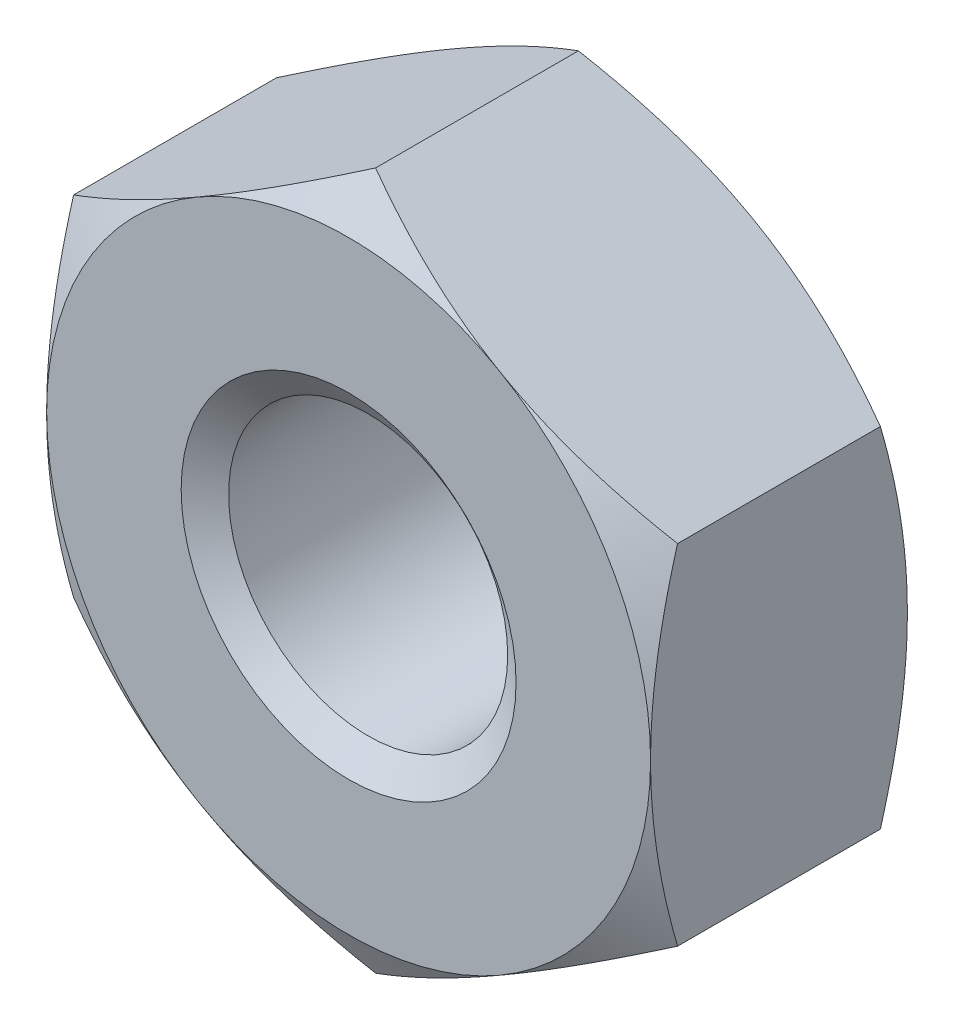
SolidWorks part; units mm, degrees
ref_plane "Plane1" through (0, 0, 0) normal (0, 0, 1) x (1, 0, 0)
ref_plane "Plane2" through (0, 0, 0) normal (0, 1, 0) x (1, 0, 0)
ref_plane "Plane3" through (0, 0, 0) normal (1, 0, 0) x (0, 0, -1)
sketch "BaseNutSke" plane through (0, 0, 0) normal (0, 0, 1) x (1, 0, 0)
  line L6 (2.705, 1.5617) -> (2.705, -1.5617)
  line L7 (-2.705, 1.5617) -> (-2.705, -1.5617)
  line L8 (2.705, 1.5617) -> (0, 3.1235)
  line L9 (0, 3.1235) -> (-2.705, 1.5617)
  line L10 (-2.705, -1.5617) -> (0, -3.1235)
  line L11 (0, -3.1235) -> (2.705, -1.5617)
  circle A0 centre (0, 0) radius 1.25
  dimension "D4" = 2.705
  dimension "Tap_drill" = 2.5
  dimension "D1" = 120
  dimension "D2" = 2.705
  dimension "D3" = 2.705
  dimension "Width_flats" = 5.41
extrude "BaseNut" add sketch "BaseNutSke" against normal blind 2.3
cosmetic thread "ThreadCosmetic"
sketch "Sketch4" plane through (0, 0, 0) normal (1, 0, 0) x (0, 0, -1)
  line L0 (2.3, 2.705) -> (2.29, 2.705)
  line L1 (2.3, 2.705) -> (2.3, 13.1235)
  line L2 (2.29, 13.1235) -> (2.3, 13.1235)
  line L3 (2.29, 13.1235) -> (2.29, 2.705)
  line L4 (0, 0) -> (34.925, 0) construction
  line L6 (2.3, 1.5617) -> (2.3, 3.1235) construction
  line L7 (0, 2.705) -> (-10, 2.705)
  line L8 (0, 1.5617) -> (0, 3.1235) construction
  line L9 (0.2416, 3.1235) -> (0.2416, 13.1235)
  line L10 (0.2416, 13.1235) -> (-10, 13.1235)
  line L11 (-10, 13.1235) -> (-10, 2.705)
  line L12 (0, 2.705) -> (0.2416, 3.1235)
  line L14 (0, 1.5617) -> (0, -1.5617) construction
  line L15 (2.3, 3.1235) -> (0, 3.1235) construction
  dimension "D1" = 2.705
  dimension "D2" = 30
  dimension "Bearing_ht" = 0.01
  dimension "D3" = 10
  dimension "D4" = 10
revolve "Bearing-Face" [suppressed] cut sketch "Sketch4" angle 360 about L4
sketch "Sketch3" plane through (0, 0, 0) normal (1, 0, 0) x (0, 0, -1)
  line L0 (2.3, 2.705) -> (2.0584, 3.1235)
  line L1 (2.0584, 3.1235) -> (2.0584, 13.1235)
  line L2 (2.0584, 13.1235) -> (12.3, 13.1235)
  line L3 (12.3, 13.1235) -> (12.3, 2.705)
  line L4 (12.3, 2.705) -> (2.3, 2.705)
  line L5 (2.3, 1.5617) -> (2.3, 3.1235) construction
  line L6 (2.3, 3.1235) -> (0, 3.1235) construction
  line L7 (0, 0) -> (38.6776, 0) construction
  line L8 (2.3, 0) -> (0, 0) construction
  line L9 (1.15, 3.1235) -> (1.15, 44.222) construction
  line L10 (0.2416, 13.1235) -> (-10, 13.1235)
  line L11 (-10, 13.1235) -> (-10, 2.705)
  line L12 (-10, 2.705) -> (0, 2.705)
  line L13 (0, 2.705) -> (0.2416, 3.1235)
  line L14 (0.2416, 3.1235) -> (0.2416, 13.1235)
  line L16 (2.3, 3.1235) -> (0, 3.1235) construction
  dimension "D1" = 2.705
  dimension "D2" = 30
  dimension "D3" = 10
  dimension "D4" = 10
revolve "Double-Chamfer" cut sketch "Sketch3" angle 360 about L7
sketch "Sketch5"
  line L0 (2.2746, 1.5) -> (2.082, 1.225)
  line L1 (2.3254, 1.5) -> (2.2746, 1.5)
  line L2 (2.3254, 1.5) -> (2.3254, 1.225)
  line L3 (2.3254, 1.225) -> (2.082, 1.225)
  line L6 (-0.0508, 1.5) -> (0, 1.5)
  line L7 (0, 1.5) -> (0.1926, 1.225)
  line L9 (0.1926, 1.225) -> (-0.0508, 1.225)
  line L10 (-0.0508, 1.225) -> (-0.0508, 1.5)
  line L11 (25.0375, 0) -> (38.388, 0) construction
  line L12 (2.3, 0) -> (0, 0) construction
pattern_linear "ThdSchPat" [suppressed]
revolve "ThreadSchematic" cut sketch "ThdSchSke"
sketch "ThdSchSke" plane through (0, 0, 0) normal (0, 1, 0) x (1, 0, 0)
  line L0 (-1.5, 0.0254) -> (-1.25, 0.2005)
  line L1 (-1.25, 0.2005) -> (-0.625, 0.2005)
  line L2 (-0.625, 0.2005) -> (-0.625, -0.1497)
  line L3 (-0.625, -0.1497) -> (-1.25, -0.1497)
  line L4 (-1.25, -0.1497) -> (-1.5, 0.0254)
  line L5 (-3.175, 0.5) -> (3.175, 0.5) construction
  line L6 (0, 0.5) -> (0, -2.9874) construction
  line L7 (0, 2.0995) -> (0, 0.1751) construction
  dimension "D1" = 35
  dimension "VeeAngle" = 70
  dimension "SideAngle" = 55
  dimension "D2" = 0.0508
  dimension "OverCut" = 1.25
  dimension "Tap_Drill" = 2.5
  dimension "Advance" = 0.4498
  dimension "Thread_major" = 3
  dimension "Num_threads" = 6
  dimension "D4" = 50
  dimension "Offset1" = 2.3254
  dimension "ThreadMajor" = 1.5
  dimension "ChamferDepth" = 0.275
  dimension "Offset2" = 2.3762
revolve "EndChamfer" cut sketch "Sketch5" angle 360 about L11
equation "\"D2@BaseNutSke\" = \"Width_flats@BaseNutSke\" / 2"
equation "\"D3@BaseNutSke\" = \"Width_flats@BaseNutSke\" / 2"
equation "\"D1@Sketch3\" = \"Width_flats@BaseNutSke\" /2"
equation "\"D1@Sketch4\" = \"D2@BaseNutSke\""
equation "\"D4@BaseNutSke\" = \"D3@BaseNutSke\""
equation "\"Thread_major@ThdSchSke\" = \"Thread_major@ThreadCosmetic\""
equation "\"Tap_drill@ThdSchSke\" = \"Tap_drill@BaseNutSke\""
equation "\"Overcut@ThdSchSke\" = \"Tap_drill@ThdSchSke\" * 0.5"
equation "\"Num_threads@ThdSchPat\" = int(  ( \"Thickness@BaseNut\" - 0.0508 ) / \"Advance@ThdSchSke\" + 0.999 )  + 1"
equation "\"Advance@ThdSchPat\" = ( \"Thickness@BaseNut\" - 0.0508 ) /  (\"Num_threads@ThdSchPat\" - 1) 'relax it"
equation "' \"Num_threads@ThdSchPat\" = \"Num_threads@ThdSchPat\" - sgn( \"Num_threads@ThdSchPat\" - 1) '---chamfered tips only---"
equation "\"ThreadMajor@Sketch5\" = \"Thread_major@ThreadCosmetic\" * 0.5"
equation "\"ChamferDepth@Sketch5\" = (\"Thread_major@ThreadCosmetic\" - \"Tap_drill@BaseNutSke\") * 0.55"
equation "\"Offset1@Sketch5\" = \"Thickness@BaseNut\" + 0.0254"
equation "\"Offset2@Sketch5\" = \"Offset1@Sketch5\" + 0.0508"
